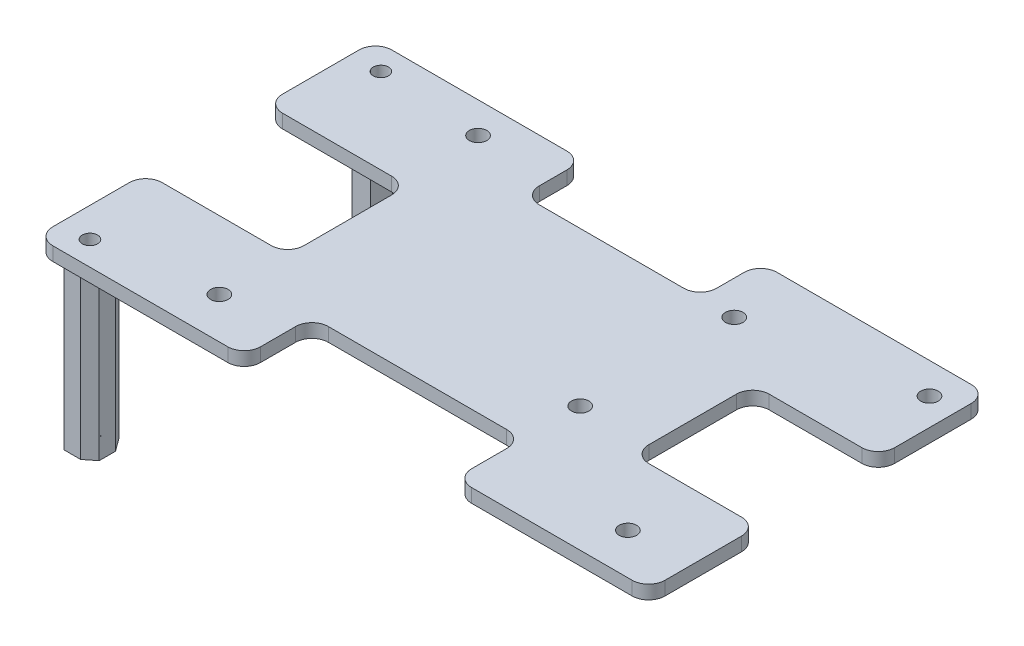
SolidWorks part; units mm, degrees
ref_plane "Alzado" through (0, 0, 0) normal (0, 0, 1) x (1, 0, 0)
ref_plane "Planta" through (0, 0, 0) normal (0, 1, 0) x (1, 0, 0)
ref_plane "Vista lateral" through (0, 0, 0) normal (1, 0, 0) x (0, 0, -1)
sketch "Croquis1" plane through (0, 0, 0) normal (0, 1, 0) x (1, 0, 0)
  line L0 (54.475, 25.34) -> (49.495, 25.34) construction
  line L3 (-54.475, -31) -> (-22.475, -31)
  line L4 (54.475, 28) -> (54.475, 14)
  line L5 (-54.475, 31) -> (54.475, -31) construction
  line L6 (-54.475, -31) -> (54.475, 31) construction
  line L7 (49.495, 25.34) -> (49.495, 31) construction
  line L8 (-54.475, 26.6) -> (-52.075, 26.6) construction
  line L9 (-52.075, 26.6) -> (-52.075, 31) construction
  line L10 (-52.075, -26.6) -> (-52.075, -31) construction
  line L11 (-33.0478, 31) -> (-33.0478, 25.34) construction
  line L12 (-33.0478, 25.34) -> (-54.475, 25.34) construction
  line L13 (19.175, 31) -> (19.175, 19.96) construction
  line L14 (19.175, 19.96) -> (54.475, 19.96) construction
  line L15 (43.175, -31) -> (43.175, -23.48) construction
  line L16 (43.175, -23.48) -> (54.475, -23.48) construction
  line L17 (-31.5278, -31) -> (-31.5278, -23.48) construction
  line L18 (-31.5278, -23.48) -> (-54.475, -23.48) construction
  line L19 (19.135, -31) -> (19.135, -8.16) construction
  line L20 (19.135, -8.16) -> (54.475, -8.16) construction
  line L21 (-52.075, -26.6) -> (-54.475, -26.6) construction
  line L22 (-54.475, 31) -> (-54.475, 11) construction
  line L23 (-54.475, 0) -> (-75.0641, 0) construction
  line L24 (-54.475, -31) -> (-54.475, -11) construction
  line L25 (0, 31) -> (0, 46.4373) construction
  line L26 (-54.475, 11) -> (-34.5278, 11)
  line L28 (-54.475, -11) -> (-34.5278, -11)
  line L29 (-31.5278, 8) -> (-31.5278, -8)
  line L30 (51.475, -11) -> (34.5278, -11)
  line L31 (31.5278, 8) -> (31.5278, -8)
  line L32 (51.475, 11) -> (34.5278, 11)
  line L34 (-54.475, 11) -> (-54.475, -11) construction
  line L35 (54.475, -14) -> (54.475, -28)
  line L36 (54.475, -11) -> (54.475, -8.16) construction
  line L37 (-54.475, -31) -> (-19.475, -31) construction
  line L38 (22.135, -31) -> (51.475, -31)
  line L40 (-19.475, -28) -> (-19.475, -21.5986)
  line L41 (-16.475, -18.5986) -> (16.135, -18.5986)
  line L42 (19.135, -28) -> (19.135, -21.5986)
  line L44 (15.9536, 31) -> (51.475, 31)
  line L46 (-19.475, 28) -> (-19.475, 22.96)
  line L47 (-16.475, 19.96) -> (9.9536, 19.96)
  line L48 (12.9536, 28) -> (12.9536, 22.96)
  line L49 (-57.475, -14) -> (-57.475, -28)
  line L53 (-57.475, 28) -> (-57.475, 14)
  line L54 (-51.475, 31) -> (54.475, 31) construction
  line L55 (-54.475, 31) -> (-22.475, 31)
  circle A0 centre (49.495, 25.34) radius 1.6
  circle A1 centre (-52.075, 26.6) radius 1.4
  circle A2 centre (-52.075, -26.6) radius 1.4
  circle A3 centre (-33.0478, 25.34) radius 1.6
  circle A4 centre (19.175, 19.96) radius 1.6
  circle A5 centre (43.175, -23.48) radius 1.6
  circle A6 centre (-31.5278, -23.48) radius 1.6
  circle A7 centre (19.135, -8.16) radius 1.6
  arc A8 (51.475, 31) -> (54.475, 28) centre (51.475, 28) cw
  arc A9 (51.475, -31) -> (54.475, -28) centre (51.475, -28) ccw
  arc A12 (-19.475, 28) -> (-22.475, 31) centre (-22.475, 28) ccw
  arc A13 (-19.475, 22.96) -> (-16.475, 19.96) centre (-16.475, 22.96) ccw
  arc A14 (9.9536, 19.96) -> (12.9536, 22.96) centre (9.9536, 22.96) ccw
  arc A15 (15.9536, 31) -> (12.9536, 28) centre (15.9536, 28) ccw
  arc A16 (51.475, 11) -> (54.475, 14) centre (51.475, 14) ccw
  arc A17 (31.5278, 8) -> (34.5278, 11) centre (34.5278, 8) cw
  arc A18 (34.5278, -11) -> (31.5278, -8) centre (34.5278, -8) cw
  arc A19 (51.475, -11) -> (54.475, -14) centre (51.475, -14) cw
  arc A20 (19.135, -28) -> (22.135, -31) centre (22.135, -28) ccw
  arc A21 (-19.475, -28) -> (-22.475, -31) centre (-22.475, -28) cw
  arc A22 (16.135, -18.5986) -> (19.135, -21.5986) centre (16.135, -21.5986) cw
  arc A23 (-19.475, -21.5986) -> (-16.475, -18.5986) centre (-16.475, -21.5986) cw
  arc A25 (-34.5278, -11) -> (-31.5278, -8) centre (-34.5278, -8) ccw
  arc A26 (-34.5278, 11) -> (-31.5278, 8) centre (-34.5278, 8) cw
  arc A27 (-54.475, -31) -> (-57.475, -28) centre (-54.475, -28) cw
  arc A28 (-54.475, -11) -> (-57.475, -14) centre (-54.475, -14) ccw
  arc A29 (-54.475, 11) -> (-57.475, 14) centre (-54.475, 14) cw
  arc A30 (-54.475, 31) -> (-57.475, 28) centre (-54.475, 28) ccw
  point P0 (0, 0)
  point P71 (-19.475, 31)
  point P80 (54.475, 11)
  point P83 (31.5278, 11)
  point P86 (31.5278, -11)
  point P98 (19.135, -18.5986)
  point P101 (-57.475, -11)
  point P106 (-31.5278, -11)
  point P109 (-31.5278, 11)
  point P115 (0, 0)
  point P116 (0, 0)
  point P117 (0, 0)
  point P118 (0, 0)
  dimension "D5" = 2.4
  dimension "D7" = 2.8
  dimension "D8" = 3.2
  dimension "D9" = 3.2
  dimension "D10" = 3.2
  dimension "D11" = 3.2
  dimension "D12" = 3.2
  dimension "D17" = 3.2
  dimension "D26" = 2.8
  dimension "D27" = 3
  dimension "D30" = 3
  dimension "D31" = 3
  dimension "D1" = 108.95
  dimension "D2" = 62
  dimension "D3" = 4.98
  dimension "D4" = 5.66
  dimension "D6" = 4.4
  dimension "D13" = 11.3
  dimension "D14" = 7.52
  dimension "D15" = 7.52
  dimension "D16" = 22.9472
  dimension "D18" = 22.84
  dimension "D19" = 35.34
  dimension "D20" = 11.04
  dimension "D21" = 35.3
  dimension "D22" = 21.4272
  dimension "D23" = 5.66
  dimension "D24" = 4.4
  dimension "D25" = 2.4
  dimension "D28" = 20
  dimension "D29" = 35
  dimension "D32" = 3
extrude "Saliente-Extruir1" add sketch "Croquis1" along normal blind 2.5
sketch "Croquis2" plane through (0, 2.5, 0) normal (0, 1, 0) x (1, 0, 0)
  line L0 (-55.475, 27.9) -> (-53.575, 29.8)
  line L1 (-50.3887, 23.0026) -> (-53.7613, 23.0026)
  line L3 (-50.575, 29.8) -> (-53.575, 29.8)
  line L5 (-50.3887, 23.0026) -> (-53.575, 29.8) construction
  line L6 (-50.575, 29.8) -> (-53.7613, 23.0026) construction
  line L8 (-55.475, 27.9) -> (-55.475, 24.9)
  line L10 (-48.6864, 28.2943) -> (-48.6864, 25.3044)
  line L11 (-55.475, 27.9) -> (-48.6864, 25.3044) construction
  line L12 (-55.475, 24.9) -> (-48.6864, 28.2943) construction
  line L13 (-50.575, 29.8) -> (-48.6864, 28.2943)
  line L14 (-48.6864, 25.3044) -> (-50.3887, 23.0026)
  line L15 (-53.7613, 23.0026) -> (-55.475, 24.9)
  line L16 (0, 0) -> (-70.434, 0) construction
  line L17 (-55.475, -27.9) -> (-53.575, -29.8)
  line L18 (-50.575, -29.8) -> (-53.575, -29.8)
  line L19 (-50.575, -29.8) -> (-48.6864, -28.2943)
  line L20 (-48.6864, -28.2943) -> (-48.6864, -25.3044)
  line L21 (-48.6864, -25.3044) -> (-50.3887, -23.0026)
  line L22 (-50.3887, -23.0026) -> (-53.7613, -23.0026)
  line L23 (-53.7613, -23.0026) -> (-55.475, -24.9)
  line L24 (-55.475, -27.9) -> (-55.475, -24.9)
  circle A2 centre (-52.075, 26.6) radius 1.4
  circle A3 centre (-52.075, -26.6) radius 1.4
  dimension "D3" = 6.8
  dimension "D4" = 3
  dimension "D5" = 6.8
  dimension "D6" = 3
extrude "Saliente-Extruir2" add sketch "Croquis2" against normal blind 32.5
